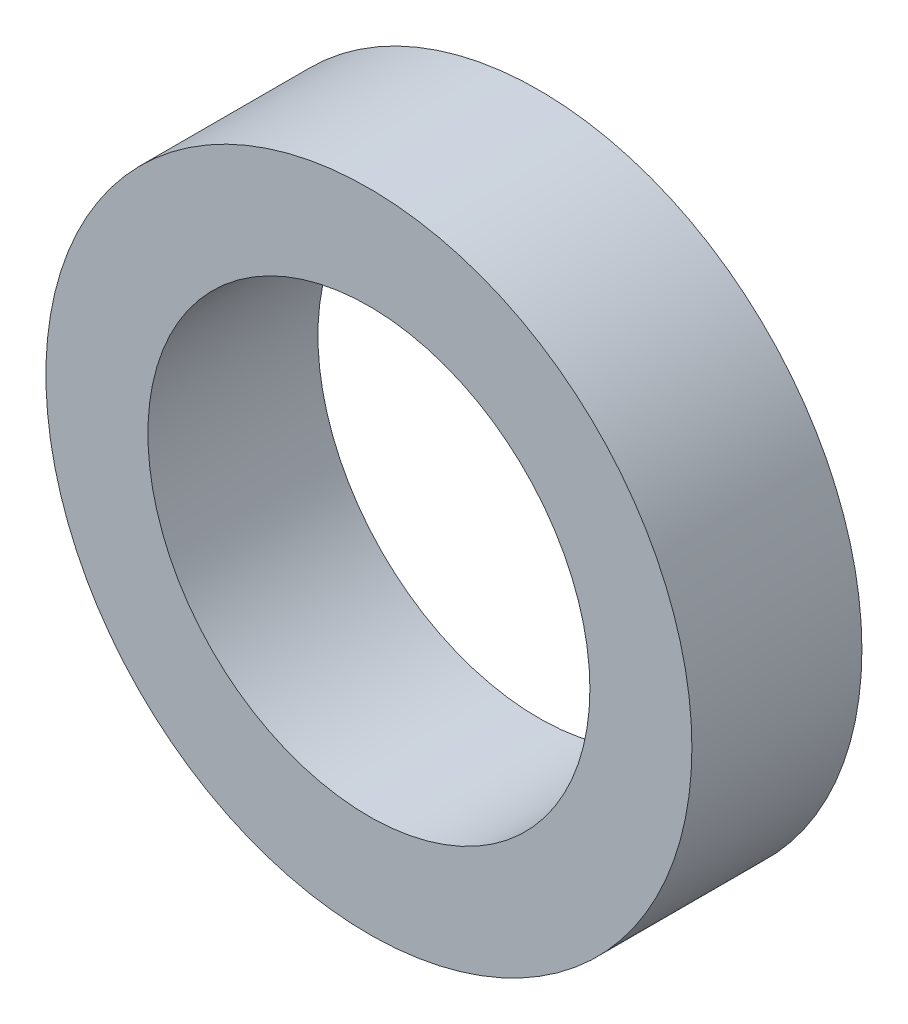
SolidWorks part; units mm, degrees
material "Plain Carbon Steel"
ref_plane "Front Plane" through (0, 0, 0) normal (0, 0, 1) x (1, 0, 0)
ref_plane "Top Plane" through (0, 0, 0) normal (0, 1, 0) x (1, 0, 0)
ref_plane "Right Plane" through (0, 0, 0) normal (1, 0, 0) x (0, 0, -1)
sketch "Sketch1" plane through (0, 0, 0) normal (0, 0, 1) x (1, 0, 0)
  circle A0 centre (0, 0) radius 6.5
  circle A1 centre (0, 0) radius 9.5
  dimension "D1" = 19
  dimension "D2" = 13
extrude "Boss-Extrude1" add sketch "Sketch1" along normal mid plane 5
